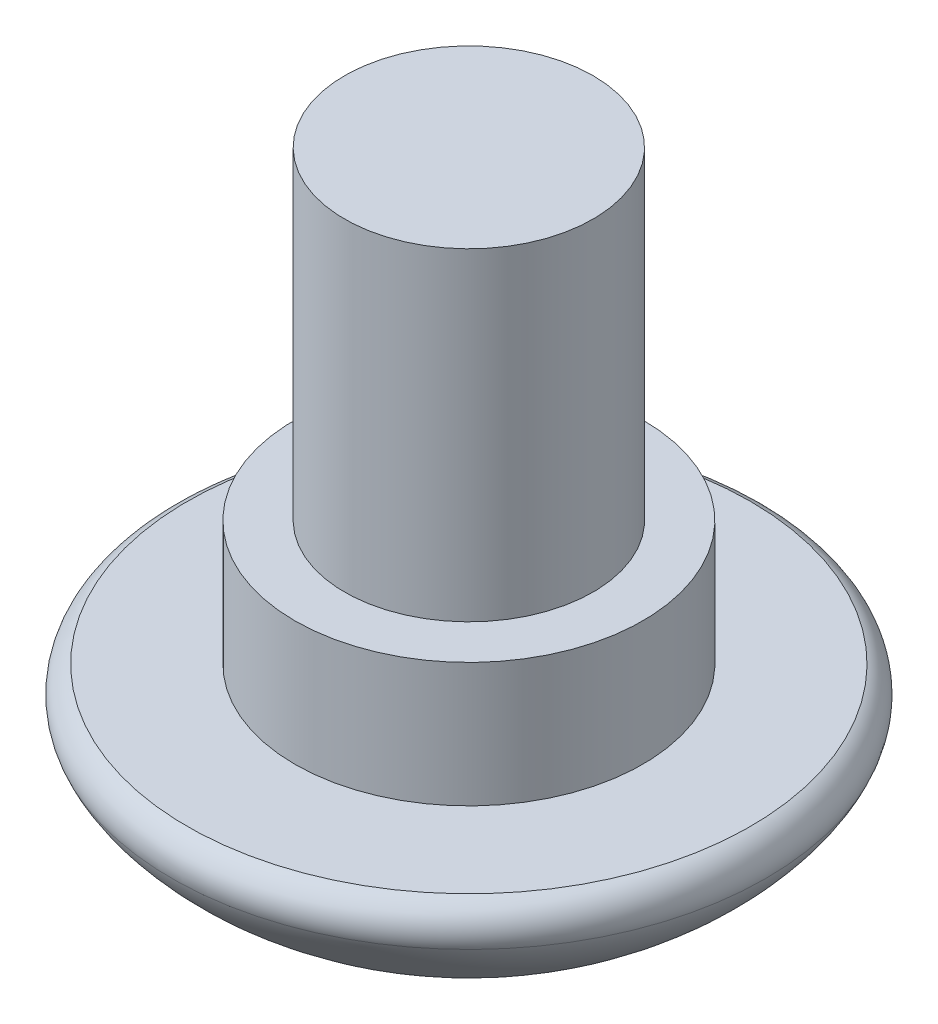
SolidWorks part; units mm, degrees
ref_plane "Front Plane" through (0, 0, 0) normal (0, 0, 1) x (1, 0, 0)
ref_plane "Top Plane" through (0, 0, 0) normal (0, 1, 0) x (1, 0, 0)
ref_plane "Right Plane" through (0, 0, 0) normal (1, 0, 0) x (0, 0, -1)
sketch "Sketch1" plane through (0, 0, 0) normal (0, 0, 1) x (1, 0, 0)
  line L0 (0, 0) -> (0, 24.6869) construction
  line L1 (0, 0) -> (0, 4)
  line L2 (0, 4) -> (5.6651, 4)
  line L3 (3.5, 4) -> (3.5, 6.5)
  line L4 (3.5, 6.5) -> (2.5, 6.5)
  line L5 (2.5, 6.5) -> (2.5, 13)
  line L6 (2.5, 13) -> (0, 13)
  line L7 (0, 13) -> (0, 4)
  arc A0 (5.6651, 4) -> (5.9758, 3.2494) centre (5.4451, 3.4693) cw
  spline S0 degree 3 poles (0, 0) (4.0572, 0.7325) (5.6918, 2.5642) (5.9758, 3.2494) knots 0 0 0 0 1 1 1 1
  dimension "D1" = 4
  dimension "D3" = 2.5
  dimension "D4" = 1
  dimension "D5" = 6.5
revolve "Revolve1" add sketch "Sketch1" angle 360 about L0
